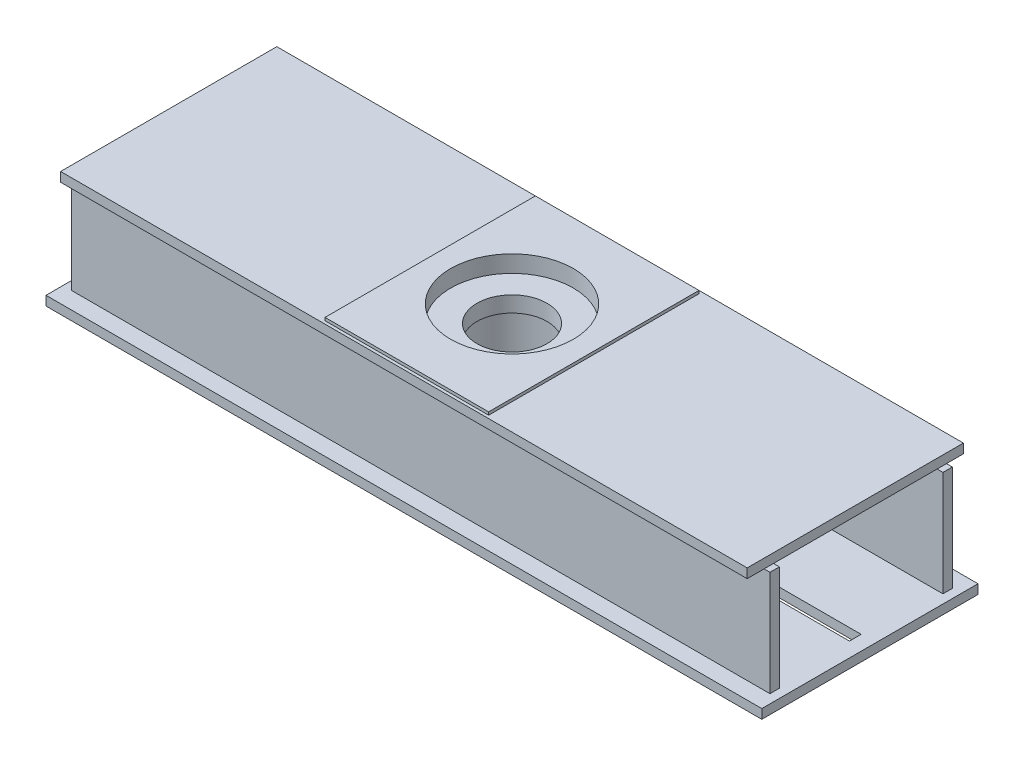
SolidWorks part; units mm, degrees
ref_plane "前视基准面" through (0, 0, 0) normal (0, 0, 1) x (1, 0, 0)
ref_plane "上视基准面" through (0, 0, 0) normal (0, 1, 0) x (1, 0, 0)
ref_plane "右视基准面" through (0, 0, 0) normal (1, 0, 0) x (0, 0, -1)
sketch "草图1" plane through (0, 0, 0) normal (0, 1, 0) x (1, 0, 0)
  line L0 (0, -845.4035) -> (0, 49154.5965) construction
  line L1 (-587.5, 185) -> (587.5, 185)
  line L2 (-587.5, 185) -> (-587.5, -185)
  line L3 (-587.5, -185) -> (587.5, -185)
  line L4 (587.5, 185) -> (587.5, -185)
  line L5 (-362.8675, 0) -> (49637.1325, 0) construction
  circle A0 centre (0, 0) radius 105
  point P10 (0, 185)
  point P13 (587.5, 0)
  dimension "D1" = 210
  dimension "D2" = 370
  dimension "D3" = 1175
extrude "凸台-拉伸1" add sketch "草图1" along normal blind 16
sketch "草图6" plane through (0, 16, 0) normal (0, 1, 0) x (1, 0, 0)
  line L0 (-1000, 0) -> (49000, 0) construction
  line L1 (-140, 180) -> (140, 180)
  line L2 (-140, 180) -> (-140, -180)
  line L3 (-140, -180) -> (140, -180)
  line L4 (140, 180) -> (140, -180)
  line L5 (0, -1000) -> (0, 49000) construction
  circle A0 centre (0, 0) radius 105
  dimension "D3" = 210
  dimension "D1" = 360
  dimension "D2" = 280
extrude "凸台-拉伸5" add sketch "草图6" along normal blind 5
sketch "草图7" plane through (0, 0, 0) normal (0, -1, 0) x (1, 0, 0)
  line L1 (-140, 140) -> (140, 140)
  line L2 (-140, 140) -> (-140, -140)
  line L3 (-140, -140) -> (140, -140)
  line L4 (140, 140) -> (140, -140)
  circle A0 centre (0, 0) radius 105
  dimension "D5" = 210
  dimension "D1" = 140
  dimension "D2" = 140
  dimension "D3" = 140
  dimension "D4" = 140
extrude "凸台-拉伸6" add sketch "草图7" along normal blind 8
sketch "草图8" plane through (0, -8, 0) normal (0, -1, 0) x (1, 0, 0)
  line L1 (-140, 140) -> (140, 140)
  line L2 (-140, 140) -> (-140, -140)
  line L3 (-140, -140) -> (140, -140)
  line L4 (140, 140) -> (140, -140)
  circle A0 centre (0, 0) radius 60
  dimension "D1" = 120
extrude "凸台-拉伸7" add sketch "草图8" along normal blind 27
sketch "草图9" plane through (0, -35, 0) normal (0, -1, 0) x (1, 0, 0)
  circle A0 centre (0, 0) radius 75
  circle A1 centre (0, 0) radius 85
  dimension "D1" = 150
  dimension "D2" = 170
extrude "凸台-拉伸8" add sketch "草图9" along normal blind 135
sketch "草图10" plane through (0, -35, 0) normal (0, -1, 0) x (-1, 0, 0)
  line L0 (362.5433, -875.257) -> (-17764.6227, 42887.5931) construction
  line L1 (61.8167, -136.1732) -> (52.5779, -140)
  line L2 (61.8167, -136.1732) -> (37.0912, -76.4804)
  line L3 (0, -1000) -> (0, 49000) construction
  line L4 (52.5779, -140) -> (27.8524, -80.3072)
  line L5 (-140, -140) -> (140, -140) construction
  circle A0 centre (0, 0) radius 85 construction
  arc A2 (37.0912, -76.4804) -> (27.8524, -80.3072) centre (0, 0) cw
  circle A3 centre (0, 0) radius 85 construction
  dimension "D1" = 5
  dimension "D2" = 5
  dimension "D4" = 22.5
extrude "凸台-拉伸9" add sketch "草图10" along normal blind 135
pattern_circular "阵列(圆周)1" count 8 over 360 about axis through (0, 0, 0) along (0, 1, 0) of "凸台-拉伸9"
sketch "草图11" plane through (0, -170, 0) normal (0, -1, 0) x (1, 0, 0)
  line L1 (140, -140) -> (-140, -140)
  line L2 (140, -140) -> (140, 140)
  line L3 (140, 140) -> (-140, 140)
  line L4 (-140, -140) -> (-140, 140)
extrude "凸台-拉伸10" add sketch "草图11" along normal blind 10
sketch "草图15" plane through (0, -180, 0) normal (0, -1, 0) x (-1, 0, 0)
  line L0 (-140, -140) -> (140, -140) construction
  line L1 (597.5, -156) -> (-597.5, -156)
  line L2 (597.5, -156) -> (597.5, -140)
  line L3 (597.5, -140) -> (-597.5, -140)
  line L4 (-597.5, -156) -> (-597.5, -140)
  line L5 (597.5, 140) -> (-597.5, 140)
  line L6 (597.5, 140) -> (597.5, 156)
  line L7 (597.5, 156) -> (-597.5, 156)
  line L8 (-597.5, 140) -> (-597.5, 156)
  line L9 (140, 140) -> (-140, 140) construction
  line L10 (0, -1000) -> (0, 49000) construction
  line L23 (-1000, 0) -> (49000, 0) construction
  dimension "D1" = 1195
  dimension "D2" = 16
extrude "凸台-拉伸14" add sketch "草图15" against normal blind 180 separate body
ref_plane "基准面1" through (0, -196, 0) normal (0, -1, 0) x (-1, 0, 0)
sketch "草图16" plane through (0, -196, 0) normal (0, -1, 0) x (1, 0, 0)
  line L1 (-612.5, 185) -> (612.5, 185)
  line L2 (-612.5, 185) -> (-612.5, -185)
  line L3 (-612.5, -185) -> (612.5, -185)
  line L4 (612.5, 185) -> (612.5, -185)
  dimension "D1" = 185
  dimension "D2" = 185
  dimension "D3" = 612.5
  dimension "D4" = 612.5
extrude "凸台-拉伸39" add sketch "草图16" against normal blind 16 separate body
sketch "草图17" plane through (0, -196, 0) normal (0, -1, 0) x (1, 0, 0)
  line L0 (-1000, 0) -> (49000, 0) construction
  line L2 (-587.5, 10) -> (-140, 10)
  line L3 (-587.5, 10) -> (-587.5, -10)
  line L4 (-587.5, -10) -> (-140, -10)
  line L5 (-140, 10) -> (-140, -10)
  line L6 (140, 10) -> (587.5, 10)
  line L7 (140, 10) -> (140, -10)
  line L8 (140, -10) -> (587.5, -10)
  line L9 (587.5, 10) -> (587.5, -10)
  dimension "D1" = 140
  dimension "D2" = 140
  dimension "D3" = 20
  dimension "D4" = 447.5
  dimension "D5" = 447.5
extrude "切除-拉伸1" cut sketch "草图17" against normal blind 16
